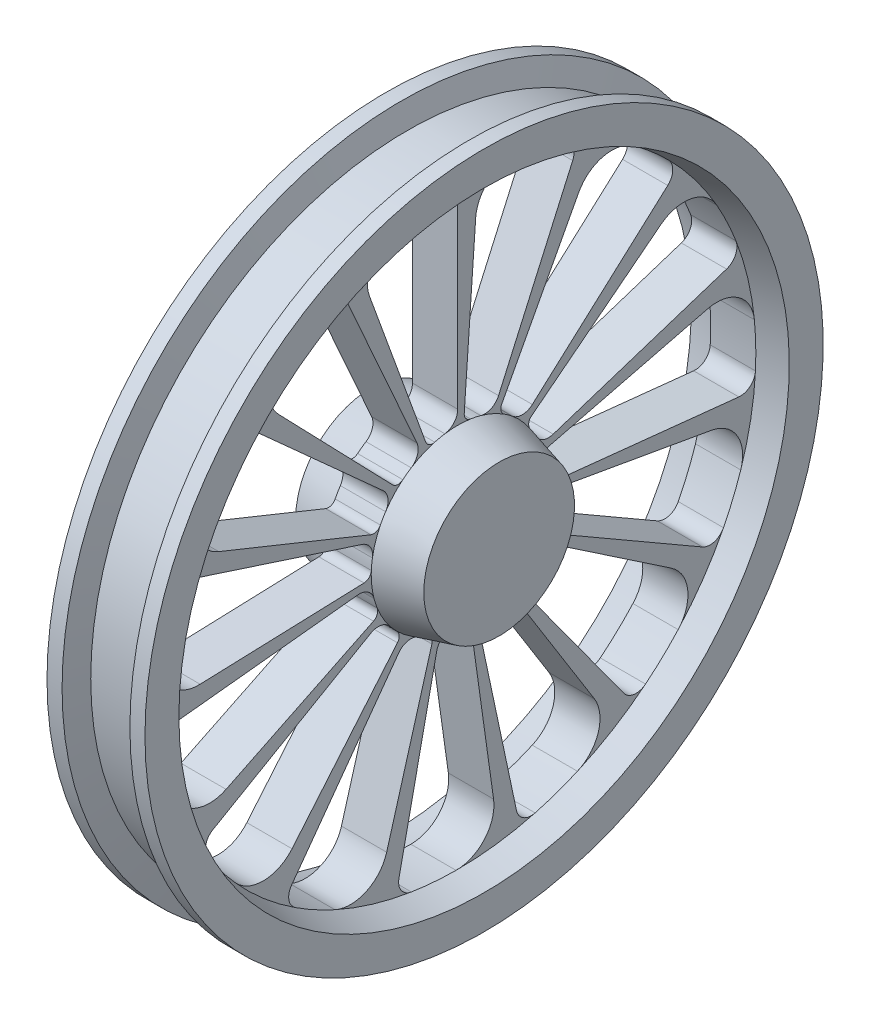
SolidWorks part; units mm, degrees
material "Alliage 1060"
ref_plane "Plan de face" through (0, 0, 0) normal (0, 0, 1) x (1, 0, 0)
ref_plane "Plan de dessus" through (0, 0, 0) normal (0, 1, 0) x (1, 0, 0)
ref_plane "Plan de droite" through (0, 0, 0) normal (1, 0, 0) x (0, 0, -1)
sketch "Esquisse2" plane through (0, 0, 0) normal (0, 0, 1) x (1, 0, 0)
  line L0 (-253.8578, 0) -> (292.7566, 0) construction
  line L1 (0, 0) -> (0, 1083.7927) construction
  line L2 (-85, 0) -> (-85, 100)
  line L3 (-85, 100) -> (-30, 114.7372)
  line L4 (-30, 114.7372) -> (-30, 395.6218)
  line L5 (-30, 395.6218) -> (-65, 405)
  line L6 (-65, 405) -> (-65, 450)
  line L7 (-65, 450) -> (-45, 450)
  line L8 (-45, 450) -> (-36.9615, 420)
  line L9 (-36.9615, 420) -> (36.9615, 420)
  line L10 (-85, 100) -> (7.799, 100) construction
  line L11 (-45, 450) -> (-45, 414.1636) construction
  line L12 (-65, 405) -> (-11.8684, 405) construction
  line L13 (30, 114.7372) -> (30, 395.6218)
  line L14 (65, 405) -> (11.8684, 405) construction
  line L15 (45, 450) -> (45, 414.1636) construction
  line L16 (85, 100) -> (-7.799, 100) construction
  line L17 (253.8578, 0) -> (-292.7566, 0) construction
  line L18 (45, 450) -> (36.9615, 420)
  line L19 (65, 450) -> (45, 450)
  line L20 (65, 405) -> (65, 450)
  line L21 (30, 395.6218) -> (65, 405)
  line L22 (85, 100) -> (30, 114.7372)
  line L23 (85, 0) -> (85, 100)
  line L24 (-85, 0) -> (85, 0)
  point P28 (0, 420)
  dimension "D1" = 900
  dimension "D2" = 15
  dimension "D3" = 20
  dimension "D4" = 30
  dimension "D5" = 15
  dimension "D6" = 15
  dimension "D7" = 130
  dimension "D8" = 170
  dimension "D9" = 60
  dimension "D10" = 170
  dimension "D11" = 100
  dimension "D12" = 45
revolve "Révolution1" add sketch "Esquisse2" angle 360 about L24
sketch "Esquisse3" plane through (-30, 0, 0) normal (-1, 0, 0) x (0, 0, 1)
  line L0 (0, 0) -> (0, 536.5395) construction
  line L1 (0, 0) -> (191.7796, 526.9103) construction
  line L2 (0, 375.0889) -> (0, 133.2446)
  line L3 (42.5253, 116.8374) -> (116.9661, 321.3617)
  line L4 (152.5624, 342.6608) -> (54.1954, 121.725)
  line L5 (86.3708, 89.4396) -> (237.5634, 246.0041)
  line L6 (278.7454, 250.9835) -> (99.02, 89.158)
  line L7 (115.2821, 46.577) -> (317.0839, 128.1102)
  line L8 (356.7308, 115.9089) -> (126.7231, 41.1748)
  line L9 (124.26, -4.3393) -> (341.7777, -11.9351)
  line L10 (373.0342, -39.2075) -> (132.5146, -13.9278)
  line L11 (111.7522, -54.5052) -> (307.375, -149.9168)
  line L12 (324.8366, -187.5445) -> (115.3932, -66.6223)
  line L13 (79.9215, -95.2467) -> (219.8244, -261.9765)
  line L14 (220.4718, -303.4533) -> (78.3192, -107.7971)
  line L15 (34.2716, -119.5192) -> (94.2641, -328.738)
  line L16 (77.9854, -366.8924) -> (27.7031, -130.3329)
  line L17 (-17.3042, -123.1257) -> (-47.5952, -338.6578)
  line L18 (-77.9854, -366.8924) -> (-27.7031, -130.3329)
  line L19 (-65.8879, -105.4427) -> (-181.225, -290.0206)
  line L20 (-220.4718, -303.4533) -> (-78.3192, -107.7971)
  line L21 (-103.079, -69.5277) -> (-283.5192, -191.2361)
  line L22 (-324.8366, -187.5445) -> (-115.3932, -66.6223)
  line L23 (-122.4468, -21.5907) -> (-336.7904, -59.3852)
  line L24 (-373.0342, -39.2075) -> (-132.5146, -13.9278)
  line L25 (-120.6424, 30.0795) -> (-331.8275, 82.7339)
  line L26 (-356.7308, 115.9089) -> (-126.7231, 41.1748)
  line L27 (-97.9779, 76.5487) -> (-269.4886, 210.5476)
  line L28 (-278.7454, 250.9835) -> (-99.02, 89.158)
  line L29 (-58.3721, 109.7819) -> (-160.5527, 301.9557)
  line L30 (-152.5624, 342.6608) -> (-54.1954, 121.725)
  line L31 (-8.6732, 124.0328) -> (-23.8557, 341.1529)
  circle A0 centre (0, 0) radius 114.7372 construction
  circle A1 centre (0, 0) radius 395.6218 construction
  arc A2 (30.4725, 110.6167) -> (17.0313, 113.4661) centre (0, 0) ccw
  arc A3 (80.1055, 387.427) -> (21.0649, 395.0606) centre (0, 0) ccw
  arc A4 (21.0649, 395.0606) -> (0, 375.0889) centre (20, 375.0889) ccw
  arc A5 (116.9661, 321.3617) -> (80.1055, 387.427) centre (69.9815, 338.4627) ccw
  arc A6 (30.4725, 110.6167) -> (42.5253, 116.8374) centre (33.1284, 120.2576) ccw
  arc A7 (17.0313, 113.4661) -> (0, 133.2446) centre (20, 133.2446) cw
  arc A8 (72.8299, 88.6591) -> (61.7097, 96.7292) centre (0, 0) ccw
  arc A9 (61.7097, 96.7292) -> (54.1954, 121.725) centre (72.4664, 113.5902) cw
  arc A10 (72.8299, 88.6591) -> (86.3708, 89.4396) centre (79.1774, 96.3862) ccw
  arc A11 (179.9294, 352.3379) -> (152.5624, 342.6608) centre (170.8333, 334.5261) ccw
  arc A12 (230.7608, 321.3504) -> (179.9294, 352.3379) centre (0, 0) ccw
  arc A13 (237.5634, 246.0041) -> (230.7608, 321.3504) centre (201.5964, 280.737) ccw
  arc A14 (102.5943, 51.3715) -> (95.7179, 63.267) centre (0, 0) ccw
  arc A15 (95.7179, 63.267) -> (99.02, 89.158) centre (112.4026, 74.2951) cw
  arc A16 (102.5943, 51.3715) -> (115.2821, 46.577) centre (111.536, 55.8488) ccw
  arc A17 (307.6824, 248.6929) -> (278.7454, 250.9835) centre (292.128, 236.1206) ccw
  arc A18 (341.5154, 199.7093) -> (307.6824, 248.6929) centre (0, 0) ccw
  arc A19 (317.0839, 128.1102) -> (341.5154, 199.7093) centre (298.3536, 174.4694) ccw
  arc A20 (114.6193, 5.2013) -> (113.1757, 18.8653) centre (0, 0) ccw
  arc A21 (113.1757, 18.8653) -> (126.7231, 41.1748) centre (132.9035, 22.1537) cw
  arc A22 (114.6193, 5.2013) -> (124.26, -4.3393) centre (124.609, 5.6547) ccw
  arc A23 (382.2344, 102.0465) -> (356.7308, 115.9089) centre (362.9111, 96.8877) ccw
  arc A24 (393.219, 43.5367) -> (382.2344, 102.0465) centre (0, 0) ccw
  arc A25 (341.7777, -11.9351) -> (393.219, 43.5367) centre (343.5226, 38.0344) ccw
  arc A26 (106.8255, -41.8682) -> (111.0643, -28.7984) centre (0, 0) ccw
  arc A27 (111.0643, -28.7984) -> (132.5146, -13.9278) centre (130.4241, -33.8183) cw
  arc A28 (106.8255, -41.8682) -> (111.7522, -54.5052) centre (116.1359, -45.5173) ccw
  arc A29 (390.6945, -62.2446) -> (373.0342, -39.2075) centre (370.9436, -59.0979) ccw
  arc A30 (376.9314, -120.1638) -> (390.6945, -62.2446) centre (0, 0) ccw
  arc A31 (307.375, -149.9168) -> (376.9314, -120.1638) centre (329.2935, -104.9771) ccw
  arc A32 (80.5606, -81.6983) -> (89.7489, -71.4826) centre (0, 0) ccw
  arc A33 (89.7489, -71.4826) -> (115.3932, -66.6223) centre (105.3932, -83.9428) cw
  arc A34 (80.5606, -81.6983) -> (79.9215, -95.2467) centre (87.5819, -88.8188) ccw
  arc A35 (331.6, -215.773) -> (324.8366, -187.5445) centre (314.8366, -204.865) ccw
  arc A36 (295.4689, -263.0869) -> (331.6, -215.773) centre (0, 0) ccw
  arc A37 (219.8244, -261.9765) -> (295.4689, -263.0869) centre (258.1266, -229.8371) ccw
  arc A38 (40.3661, -107.4021) -> (52.9151, -101.8067) centre (0, 0) ccw
  arc A39 (52.9151, -101.8067) -> (78.3192, -107.7971) centre (62.1389, -119.5528) cw
  arc A40 (40.3661, -107.4021) -> (34.2716, -119.5192) centre (43.8842, -116.7628) ccw
  arc A41 (215.1689, -331.9924) -> (220.4718, -303.4533) centre (204.2914, -315.209) ccw
  arc A42 (162.9172, -360.5199) -> (215.1689, -331.9924) centre (0, 0) ccw
  arc A43 (94.2641, -328.738) -> (162.9172, -360.5199) centre (142.3272, -314.9562) ccw
  arc A44 (-6.8081, -114.535) -> (6.9319, -114.5276) centre (0, 0) ccw
  arc A45 (6.9319, -114.5276) -> (27.7031, -130.3329) centre (8.1402, -134.4911) cw
  arc A46 (-6.8081, -114.535) -> (-17.3042, -123.1257) centre (-7.4015, -124.5174) ccw
  arc A47 (61.5331, -390.8072) -> (77.9854, -366.8924) centre (58.4224, -371.0506) ccw
  arc A48 (2.1956, -395.6157) -> (61.5331, -390.8072) centre (0, 0) ccw
  arc A49 (-47.5952, -338.6578) -> (2.1956, -395.6157) centre (1.9182, -345.6165) ccw
  arc A50 (-52.8051, -101.8638) -> (-40.25, -107.4456) centre (0, 0) ccw
  arc A51 (-40.25, -107.4456) -> (-27.7031, -130.3329) centre (-47.2661, -126.1746) cw
  arc A52 (-52.8051, -101.8638) -> (-65.8879, -105.4427) centre (-57.4074, -110.7419) ccw
  arc A53 (-102.7423, -382.0479) -> (-77.9854, -366.8924) centre (-97.5483, -362.7341) ccw
  arc A54 (-158.9056, -362.306) -> (-102.7423, -382.0479) centre (0, 0) ccw
  arc A55 (-181.225, -290.0206) -> (-158.9056, -362.306) centre (-138.8226, -316.5165) ccw
  arc A56 (-89.6717, -71.5795) -> (-80.4723, -81.7853) centre (0, 0) ccw
  arc A57 (-80.4723, -81.7853) -> (-78.3192, -107.7971) centre (-94.4995, -96.0414) cw
  arc A58 (-89.6717, -71.5795) -> (-103.079, -69.5277) centre (-97.4871, -77.818) ccw
  arc A59 (-249.2526, -307.2291) -> (-220.4718, -303.4533) centre (-236.6521, -291.6976) ccw
  arc A60 (-292.5306, -266.3502) -> (-249.2526, -307.2291) centre (0, 0) ccw
  arc A61 (-283.5192, -191.2361) -> (-292.5306, -266.3502) centre (-255.5596, -232.688) ccw
  arc A62 (-111.0331, -28.9183) -> (-106.7802, -41.9836) centre (0, 0) ccw
  arc A63 (-106.7802, -41.9836) -> (-115.3932, -66.6223) centre (-125.3932, -49.3018) cw
  arc A64 (-111.0331, -28.9183) -> (-122.4468, -21.5907) centre (-120.7103, -31.4387) ccw
  arc A65 (-352.6649, -179.2876) -> (-324.8366, -187.5445) centre (-334.8366, -170.224) ccw
  arc A66 (-375.5744, -124.3402) -> (-352.6649, -179.2876) centre (0, 0) ccw
  arc A67 (-336.7904, -59.3852) -> (-375.5744, -124.3402) centre (-328.108, -108.6256) ccw
  arc A68 (-113.196, 18.743) -> (-114.6248, 5.0775) centre (0, 0) ccw
  arc A69 (-114.6248, 5.0775) -> (-132.5146, -13.9278) centre (-134.6052, 5.9626) cw
  arc A70 (-113.196, 18.743) -> (-120.6424, 30.0795) centre (-123.0616, 20.3766) ccw
  arc A71 (-395.0983, -20.3456) -> (-373.0342, -39.2075) centre (-375.1247, -19.317) ccw
  arc A72 (-393.678, 39.1695) -> (-395.0983, -20.3456) centre (0, 0) ccw
  arc A73 (-331.8275, 82.7339) -> (-393.678, 39.1695) centre (-343.9236, 34.2191) ccw
  arc A74 (-95.7862, 63.1635) -> (-102.6498, 51.2607) centre (0, 0) ccw
  arc A75 (-102.6498, 51.2607) -> (-126.7231, 41.1748) centre (-120.5428, 60.196) cw
  arc A76 (-95.7862, 63.1635) -> (-97.9779, 76.5487) centre (-104.1345, 68.6686) ccw
  arc A77 (-369.2155, 142.1143) -> (-356.7308, 115.9089) centre (-350.5505, 134.93) ccw
  arc A78 (-343.7111, 195.9064) -> (-369.2155, 142.1143) centre (0, 0) ccw
  arc A79 (-269.4886, 210.5476) -> (-343.7111, 195.9064) centre (-300.2717, 171.1471) ccw
  arc A80 (-61.8141, 96.6625) -> (-72.9256, 88.5804) centre (0, 0) ccw
  arc A81 (-72.9256, 88.5804) -> (-99.02, 89.158) centre (-85.6374, 104.0209) cw
  arc A82 (-61.8141, 96.6625) -> (-58.3721, 109.7819) centre (-67.2016, 105.0872) ccw
  arc A83 (-279.4921, 280.0014) -> (-278.7454, 250.9835) centre (-265.3628, 265.8464) ccw
  arc A84 (-234.3134, 318.7692) -> (-279.4921, 280.0014) centre (0, 0) ccw
  arc A85 (-160.5527, 301.9557) -> (-234.3134, 318.7692) centre (-204.7001, 278.4821) ccw
  arc A86 (-17.1538, 113.4477) -> (-30.592, 110.5837) centre (0, 0) ccw
  arc A87 (-30.592, 110.5837) -> (-54.1954, 121.725) centre (-35.9245, 129.8597) cw
  arc A88 (-17.1538, 113.4477) -> (-8.6732, 124.0328) centre (-18.6489, 123.3353) ccw
  arc A89 (-141.4419, 369.4737) -> (-152.5624, 342.6608) centre (-134.2915, 350.7955) ccw
  arc A90 (-84.4008, 386.514) -> (-141.4419, 369.4737) centre (0, 0) ccw
  arc A91 (-23.8557, 341.1529) -> (-84.4008, 386.514) centre (-73.7339, 337.6651) ccw
  point P12 (0, 395.6218)
  point P15 (135.3106, 371.7629)
  point P18 (39.2424, 107.8177)
  point P21 (0, 114.7372)
  point P193 (0, 0)
  dimension "D2" = 20
  dimension "D3" = 50
  dimension "D4" = 10
  dimension "D5" = 20
  dimension "D1" = 20
  dimension "D6" = 15
extrude "Enlèv. mat.-Extru.1" cut sketch "Esquisse3" against normal through all
equation "\"A\"= 130"
equation "\"B\"= 900"
equation "\"D1@Esquisse2\"=\"B\""
equation "\"D7@Esquisse2\"=\"A\""
equation "\"D8@Esquisse2\"=\"A\" +40"
